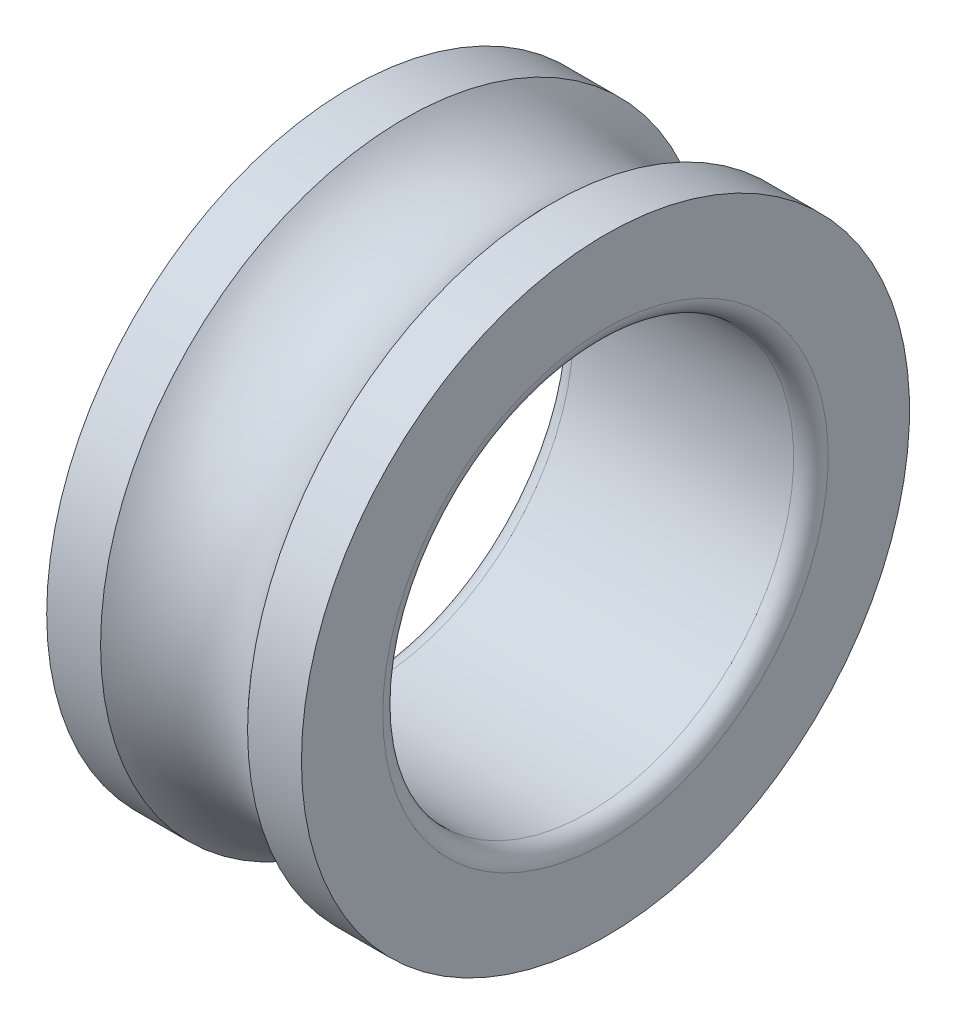
SolidWorks part; units mm, degrees
ref_plane "Front Plane" through (0, 0, 0) normal (0, 0, 1) x (1, 0, 0)
ref_plane "Top Plane" through (0, 0, 0) normal (0, 1, 0) x (1, 0, 0)
ref_plane "Right Plane" through (0, 0, 0) normal (1, 0, 0) x (0, 0, -1)
sketch "Sketch1" plane through (0, 0, 0) normal (0, 0, 1) x (1, 0, 0)
  line L0 (0, 0) -> (0, 45) construction
  line L1 (0, 0) -> (33.2034, 0) construction
  line L2 (-15.5, 37) -> (-8.9443, 37)
  line L3 (-15.5, 37) -> (-15.5, 27.1)
  line L4 (-13.4, 25) -> (13.4, 25)
  line L5 (15.5, 37) -> (15.5, 27.1)
  line L6 (8.9443, 37) -> (15.5, 37)
  arc A0 (-8.9443, 37) -> (8.9443, 37) centre (0, 45) ccw
  arc A1 (13.4, 25) -> (15.5, 27.1) centre (13.4, 27.1) ccw
  arc A2 (-15.5, 27.1) -> (-13.4, 25) centre (-13.4, 27.1) ccw
  dimension "D4" = 12
  dimension "D6" = 2.1
  dimension "D1" = 37
  dimension "D2" = 25
  dimension "D3" = 31
  dimension "D5" = 8
revolve "Revolve1" add sketch "Sketch1" angle 360 about L1
